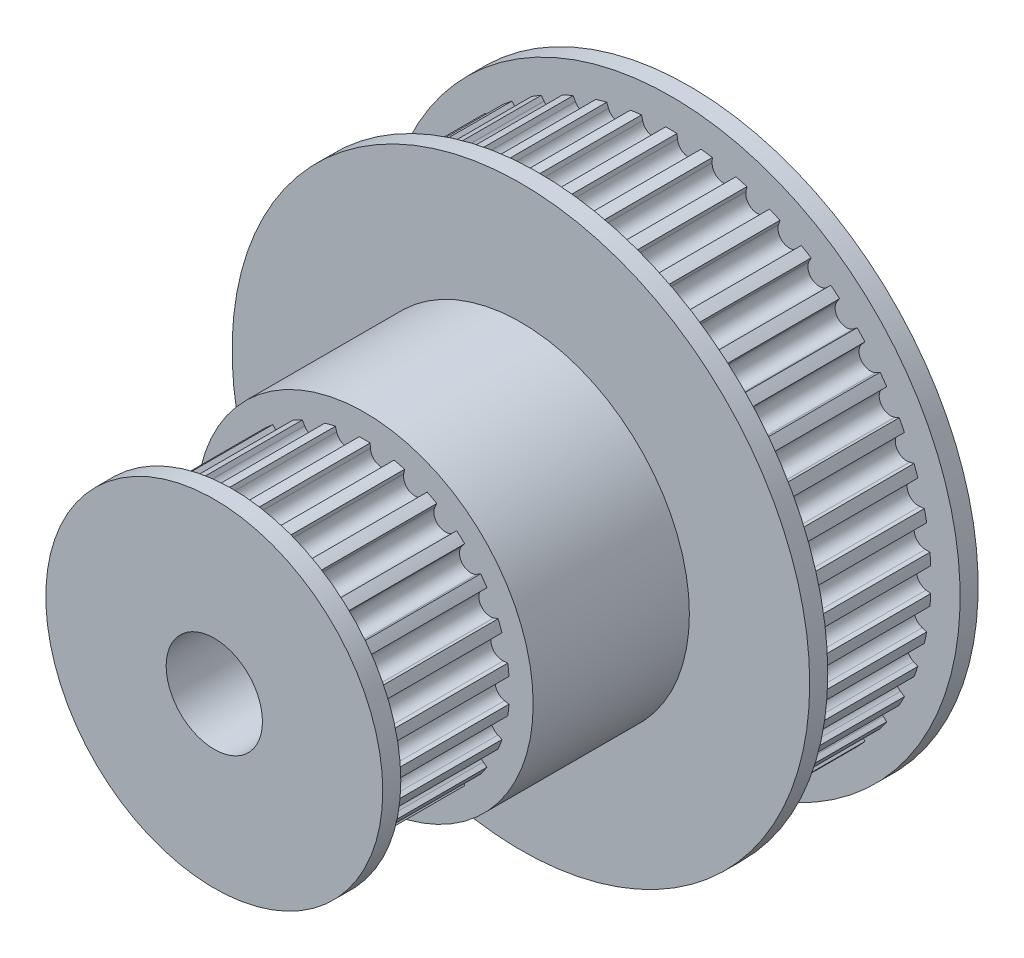
SolidWorks part; units mm, degrees
material "PLA Density Only"
ref_plane "Front Plane" through (0, 0, 0) normal (0, 0, 1) x (1, 0, 0)
ref_plane "Top Plane" through (0, 0, 0) normal (0, 1, 0) x (1, 0, 0)
ref_plane "Right Plane" through (0, 0, 0) normal (1, 0, 0) x (0, 0, -1)
sketch "Sketch1" plane through (0, 0, 0) normal (0, 0, 1) x (1, 0, 0)
  line L0 (-0.4734, 21.5748) -> (-0.5099, 21.1906)
  line L1 (-2.3803, 21.0626) -> (-2.4688, 21.4383)
  line L2 (-3.4068, 21.3094) -> (-3.3906, 20.9238)
  line L3 (-5.2262, 20.5423) -> (-5.3649, 20.9025)
  line L4 (-6.2767, 20.647) -> (-6.2081, 20.2672)
  line L5 (-7.9747, 19.6394) -> (-8.1612, 19.9773)
  line L6 (-9.0297, 19.6) -> (-8.91, 19.2331)
  line L7 (-10.5747, 18.3706) -> (-10.8054, 18.6799)
  line L8 (-11.6144, 18.188) -> (-11.4459, 17.8407)
  line L9 (-12.9776, 16.7595) -> (-13.2484, 17.0346)
  line L10 (-13.9828, 16.4371) -> (-13.7686, 16.116)
  line L11 (-15.1388, 14.8363) -> (-15.4445, 15.0719)
  line L12 (-16.0908, 14.38) -> (-15.8349, 14.0911)
  line L13 (-17.0181, 12.6367) -> (-17.353, 12.8285)
  line L14 (-17.899, 12.055) -> (-17.6061, 11.8037)
  line L15 (-18.5802, 10.2017) -> (-18.9381, 10.3462)
  line L16 (-19.3738, 9.5055) -> (-19.0494, 9.2964)
  line L17 (-19.7963, 7.5767) -> (-20.1706, 7.671)
  line L18 (-20.4876, 6.7789) -> (-20.1378, 6.6159)
  line L19 (-20.6436, 4.8105) -> (-21.0272, 4.853)
  line L20 (-21.2199, 3.926) -> (-20.8511, 3.8122)
  line L21 (-21.1064, 1.9548) -> (-21.4922, 1.9446)
  line L22 (-21.5568, 1) -> (-21.176, 0.9374)
  line L23 (-21.176, -0.9374) -> (-21.5568, -1)
  line L24 (-21.4922, -1.9446) -> (-21.1064, -1.9548)
  line L25 (-20.8511, -3.8122) -> (-21.2199, -3.926)
  line L26 (-21.0272, -4.853) -> (-20.6436, -4.8105)
  line L27 (-20.1378, -6.6159) -> (-20.4876, -6.7789)
  line L28 (-20.1706, -7.671) -> (-19.7963, -7.5767)
  line L29 (-19.0494, -9.2964) -> (-19.3738, -9.5055)
  line L30 (-18.9381, -10.3462) -> (-18.5802, -10.2017)
  line L31 (-17.6061, -11.8037) -> (-17.899, -12.055)
  line L32 (-17.353, -12.8285) -> (-17.0181, -12.6367)
  line L33 (-15.8349, -14.0911) -> (-16.0908, -14.38)
  line L34 (-15.4445, -15.0719) -> (-15.1388, -14.8363)
  line L35 (-13.7686, -16.116) -> (-13.9828, -16.4371)
  line L36 (-13.2484, -17.0346) -> (-12.9776, -16.7595)
  line L37 (-11.4459, -17.8407) -> (-11.6144, -18.188)
  line L38 (-10.8054, -18.6799) -> (-10.5747, -18.3706)
  line L39 (-8.91, -19.2331) -> (-9.0297, -19.6)
  line L40 (-8.1612, -19.9773) -> (-7.9747, -19.6394)
  line L41 (-6.2081, -20.2672) -> (-6.2767, -20.647)
  line L42 (-5.3649, -20.9025) -> (-5.2262, -20.5423)
  line L43 (-3.3906, -20.9238) -> (-3.4068, -21.3094)
  line L44 (-2.4688, -21.4383) -> (-2.3803, -21.0626)
  line L45 (-0.5099, -21.1906) -> (-0.4734, -21.5748)
  line L46 (0.4734, -21.5748) -> (0.5099, -21.1906)
  line L47 (2.3803, -21.0626) -> (2.4688, -21.4383)
  line L48 (3.4068, -21.3094) -> (3.3906, -20.9238)
  line L49 (5.2262, -20.5423) -> (5.3649, -20.9025)
  line L50 (6.2767, -20.647) -> (6.2081, -20.2672)
  line L51 (7.9747, -19.6394) -> (8.1612, -19.9773)
  line L52 (9.0297, -19.6) -> (8.91, -19.2331)
  line L53 (10.5747, -18.3706) -> (10.8054, -18.6799)
  line L54 (11.6144, -18.188) -> (11.4459, -17.8407)
  line L55 (12.9776, -16.7595) -> (13.2484, -17.0346)
  line L56 (13.9828, -16.4371) -> (13.7686, -16.116)
  line L57 (15.1388, -14.8363) -> (15.4445, -15.0719)
  line L58 (16.0908, -14.38) -> (15.8349, -14.0911)
  line L59 (17.0181, -12.6367) -> (17.353, -12.8285)
  line L60 (17.899, -12.055) -> (17.6061, -11.8037)
  line L61 (18.5802, -10.2017) -> (18.9381, -10.3462)
  line L62 (19.3738, -9.5055) -> (19.0494, -9.2964)
  line L63 (19.7963, -7.5767) -> (20.1706, -7.671)
  line L64 (20.4876, -6.7789) -> (20.1378, -6.6159)
  line L65 (20.6436, -4.8105) -> (21.0272, -4.853)
  line L66 (21.2199, -3.926) -> (20.8511, -3.8122)
  line L67 (21.1064, -1.9548) -> (21.4922, -1.9446)
  line L68 (21.5568, -1) -> (21.176, -0.9374)
  line L69 (21.176, 0.9374) -> (21.5568, 1)
  line L70 (21.4922, 1.9446) -> (21.1064, 1.9548)
  line L71 (20.8511, 3.8122) -> (21.2199, 3.926)
  line L72 (21.0272, 4.853) -> (20.6436, 4.8105)
  line L73 (20.1378, 6.6159) -> (20.4876, 6.7789)
  line L74 (20.1706, 7.671) -> (19.7963, 7.5767)
  line L75 (19.0494, 9.2964) -> (19.3738, 9.5055)
  line L76 (18.9381, 10.3462) -> (18.5802, 10.2017)
  line L77 (17.6061, 11.8037) -> (17.899, 12.055)
  line L78 (17.353, 12.8285) -> (17.0181, 12.6367)
  line L79 (15.8349, 14.0911) -> (16.0908, 14.38)
  line L80 (15.4445, 15.0719) -> (15.1388, 14.8363)
  line L81 (13.7686, 16.116) -> (13.9828, 16.4371)
  line L82 (13.2484, 17.0346) -> (12.9776, 16.7595)
  line L83 (11.4459, 17.8407) -> (11.6144, 18.188)
  line L84 (10.8054, 18.6799) -> (10.5747, 18.3706)
  line L85 (8.91, 19.2331) -> (9.0297, 19.6)
  line L86 (8.1612, 19.9773) -> (7.9747, 19.6394)
  line L87 (6.2081, 20.2672) -> (6.2767, 20.647)
  line L88 (5.3649, 20.9025) -> (5.2262, 20.5423)
  line L89 (3.3906, 20.9238) -> (3.4068, 21.3094)
  line L90 (2.4688, 21.4383) -> (2.3803, 21.0626)
  line L91 (0.5099, 21.1906) -> (0.4734, 21.5748)
  circle A0 centre (0, 0) radius 4
  arc A1 (-0.5099, 21.1906) -> (-2.3803, 21.0626) centre (-1.4556, 21.2803) cw
  arc A2 (-2.4688, 21.4383) -> (-3.4068, 21.3094) centre (0, 0) ccw
  arc A3 (-3.3906, 20.9238) -> (-5.2262, 20.5423) centre (-4.3397, 20.8839) cw
  arc A4 (-5.3649, 20.9025) -> (-6.2767, 20.647) centre (0, 0) ccw
  arc A5 (-6.2081, 20.2672) -> (-7.9747, 19.6394) centre (-7.143, 20.0984) cw
  arc A6 (-8.1612, 19.9773) -> (-9.0297, 19.6) centre (0, 0) ccw
  arc A7 (-8.91, 19.2331) -> (-10.5747, 18.3706) centre (-9.8132, 18.9386) cw
  arc A8 (-10.8054, 18.6799) -> (-11.6144, 18.188) centre (0, 0) ccw
  arc A9 (-11.4459, 17.8407) -> (-12.9776, 16.7595) centre (-12.3006, 17.426) cw
  arc A10 (-13.2484, 17.0346) -> (-13.9828, 16.4371) centre (0, 0) ccw
  arc A11 (-13.7686, 16.116) -> (-15.1388, 14.8363) centre (-14.5589, 15.5887) cw
  arc A12 (-15.4445, 15.0719) -> (-16.0908, 14.38) centre (0, 0) ccw
  arc A13 (-15.8349, 14.0911) -> (-17.0181, 12.6367) centre (-16.5459, 13.4611) cw
  arc A14 (-17.353, 12.8285) -> (-17.899, 12.055) centre (0, 0) ccw
  arc A15 (-17.6061, 11.8037) -> (-18.5802, 10.2017) centre (-18.2248, 11.0827) cw
  arc A16 (-18.9381, 10.3462) -> (-19.3738, 9.5055) centre (0, 0) ccw
  arc A17 (-19.0494, 9.2964) -> (-19.7963, 7.5767) centre (-19.5641, 8.4979) cw
  arc A18 (-20.1706, 7.671) -> (-20.4876, 6.7789) centre (0, 0) ccw
  arc A19 (-20.1378, 6.6159) -> (-20.6436, 4.8105) centre (-20.539, 5.7548) cw
  arc A20 (-21.0272, 4.853) -> (-21.2199, 3.926) centre (0, 0) ccw
  arc A21 (-20.8511, 3.8122) -> (-21.1064, 1.9548) centre (-21.1313, 2.9044) cw
  arc A22 (-21.4922, 1.9446) -> (-21.5568, 1) centre (0, 0) ccw
  arc A23 (-21.176, 0.9374) -> (-21.176, -0.9374) centre (-21.33, 0) cw
  arc A24 (-21.5568, -1) -> (-21.4922, -1.9446) centre (0, 0) ccw
  arc A25 (-21.1064, -1.9548) -> (-20.8511, -3.8122) centre (-21.1313, -2.9044) cw
  arc A26 (-21.2199, -3.926) -> (-21.0272, -4.853) centre (0, 0) ccw
  arc A27 (-20.6436, -4.8105) -> (-20.1378, -6.6159) centre (-20.539, -5.7548) cw
  arc A28 (-20.4876, -6.7789) -> (-20.1706, -7.671) centre (0, 0) ccw
  arc A29 (-19.7963, -7.5767) -> (-19.0494, -9.2964) centre (-19.5641, -8.4979) cw
  arc A30 (-19.3738, -9.5055) -> (-18.9381, -10.3462) centre (0, 0) ccw
  arc A31 (-18.5802, -10.2017) -> (-17.6061, -11.8037) centre (-18.2248, -11.0827) cw
  arc A32 (-17.899, -12.055) -> (-17.353, -12.8285) centre (0, 0) ccw
  arc A33 (-17.0181, -12.6367) -> (-15.8349, -14.0911) centre (-16.5459, -13.4611) cw
  arc A34 (-16.0908, -14.38) -> (-15.4445, -15.0719) centre (0, 0) ccw
  arc A35 (-15.1388, -14.8363) -> (-13.7686, -16.116) centre (-14.5589, -15.5887) cw
  arc A36 (-13.9828, -16.4371) -> (-13.2484, -17.0346) centre (0, 0) ccw
  arc A37 (-12.9776, -16.7595) -> (-11.4459, -17.8407) centre (-12.3006, -17.426) cw
  arc A38 (-11.6144, -18.188) -> (-10.8054, -18.6799) centre (0, 0) ccw
  arc A39 (-10.5747, -18.3706) -> (-8.91, -19.2331) centre (-9.8132, -18.9386) cw
  arc A40 (-9.0297, -19.6) -> (-8.1612, -19.9773) centre (0, 0) ccw
  arc A41 (-7.9747, -19.6394) -> (-6.2081, -20.2672) centre (-7.143, -20.0984) cw
  arc A42 (-6.2767, -20.647) -> (-5.3649, -20.9025) centre (0, 0) ccw
  arc A43 (-5.2262, -20.5423) -> (-3.3906, -20.9238) centre (-4.3397, -20.8839) cw
  arc A44 (-3.4068, -21.3094) -> (-2.4688, -21.4383) centre (0, 0) ccw
  arc A45 (-2.3803, -21.0626) -> (-0.5099, -21.1906) centre (-1.4556, -21.2803) cw
  arc A46 (-0.4734, -21.5748) -> (0.4734, -21.5748) centre (0, 0) ccw
  arc A47 (0.5099, -21.1906) -> (2.3803, -21.0626) centre (1.4556, -21.2803) cw
  arc A48 (2.4688, -21.4383) -> (3.4068, -21.3094) centre (0, 0) ccw
  arc A49 (3.3906, -20.9238) -> (5.2262, -20.5423) centre (4.3397, -20.8839) cw
  arc A50 (5.3649, -20.9025) -> (6.2767, -20.647) centre (0, 0) ccw
  arc A51 (6.2081, -20.2672) -> (7.9747, -19.6394) centre (7.143, -20.0984) cw
  arc A52 (8.1612, -19.9773) -> (9.0297, -19.6) centre (0, 0) ccw
  arc A53 (8.91, -19.2331) -> (10.5747, -18.3706) centre (9.8132, -18.9386) cw
  arc A54 (10.8054, -18.6799) -> (11.6144, -18.188) centre (0, 0) ccw
  arc A55 (11.4459, -17.8407) -> (12.9776, -16.7595) centre (12.3006, -17.426) cw
  arc A56 (13.2484, -17.0346) -> (13.9828, -16.4371) centre (0, 0) ccw
  arc A57 (13.7686, -16.116) -> (15.1388, -14.8363) centre (14.5589, -15.5887) cw
  arc A58 (15.4445, -15.0719) -> (16.0908, -14.38) centre (0, 0) ccw
  arc A59 (15.8349, -14.0911) -> (17.0181, -12.6367) centre (16.5459, -13.4611) cw
  arc A60 (17.353, -12.8285) -> (17.899, -12.055) centre (0, 0) ccw
  arc A61 (17.6061, -11.8037) -> (18.5802, -10.2017) centre (18.2248, -11.0827) cw
  arc A62 (18.9381, -10.3462) -> (19.3738, -9.5055) centre (0, 0) ccw
  arc A63 (19.0494, -9.2964) -> (19.7963, -7.5767) centre (19.5641, -8.4979) cw
  arc A64 (20.1706, -7.671) -> (20.4876, -6.7789) centre (0, 0) ccw
  arc A65 (20.1378, -6.6159) -> (20.6436, -4.8105) centre (20.539, -5.7548) cw
  arc A66 (21.0272, -4.853) -> (21.2199, -3.926) centre (0, 0) ccw
  arc A67 (20.8511, -3.8122) -> (21.1064, -1.9548) centre (21.1313, -2.9044) cw
  arc A68 (21.4922, -1.9446) -> (21.5568, -1) centre (0, 0) ccw
  arc A69 (21.176, -0.9374) -> (21.176, 0.9374) centre (21.33, 0) cw
  arc A70 (21.5568, 1) -> (21.4922, 1.9446) centre (0, 0) ccw
  arc A71 (21.1064, 1.9548) -> (20.8511, 3.8122) centre (21.1313, 2.9044) cw
  arc A72 (21.2199, 3.926) -> (21.0272, 4.853) centre (0, 0) ccw
  arc A73 (20.6436, 4.8105) -> (20.1378, 6.6159) centre (20.539, 5.7548) cw
  arc A74 (20.4876, 6.7789) -> (20.1706, 7.671) centre (0, 0) ccw
  arc A75 (19.7963, 7.5767) -> (19.0494, 9.2964) centre (19.5641, 8.4979) cw
  arc A76 (19.3738, 9.5055) -> (18.9381, 10.3462) centre (0, 0) ccw
  arc A77 (18.5802, 10.2017) -> (17.6061, 11.8037) centre (18.2248, 11.0827) cw
  arc A78 (17.899, 12.055) -> (17.353, 12.8285) centre (0, 0) ccw
  arc A79 (17.0181, 12.6367) -> (15.8349, 14.0911) centre (16.5459, 13.4611) cw
  arc A80 (16.0908, 14.38) -> (15.4445, 15.0719) centre (0, 0) ccw
  arc A81 (15.1388, 14.8363) -> (13.7686, 16.116) centre (14.5589, 15.5887) cw
  arc A82 (13.9828, 16.4371) -> (13.2484, 17.0346) centre (0, 0) ccw
  arc A83 (12.9776, 16.7595) -> (11.4459, 17.8407) centre (12.3006, 17.426) cw
  arc A84 (11.6144, 18.188) -> (10.8054, 18.6799) centre (0, 0) ccw
  arc A85 (10.5747, 18.3706) -> (8.91, 19.2331) centre (9.8132, 18.9386) cw
  arc A86 (9.0297, 19.6) -> (8.1612, 19.9773) centre (0, 0) ccw
  arc A87 (7.9747, 19.6394) -> (6.2081, 20.2672) centre (7.143, 20.0984) cw
  arc A88 (6.2767, 20.647) -> (5.3649, 20.9025) centre (0, 0) ccw
  arc A89 (5.2262, 20.5423) -> (3.3906, 20.9238) centre (4.3397, 20.8839) cw
  arc A90 (3.4068, 21.3094) -> (2.4688, 21.4383) centre (0, 0) ccw
  arc A91 (2.3803, 21.0626) -> (0.5099, 21.1906) centre (1.4556, 21.2803) cw
  arc A92 (0.4734, 21.5748) -> (-0.4734, 21.5748) centre (0, 0) ccw
extrude "Boss-Extrude1" add sketch "Sketch1" along normal blind 11
ref_plane "Plane1" through (0, 0, 36.48) normal (0, 0, 1) x (1, 0, 0)
sketch "Sketch2" plane through (0, 0, 36.48) normal (0, 0, 1) x (1, 0, 0)
  line L0 (-0.4529, 12.0265) -> (-0.4717, 11.6515)
  line L1 (-2.3304, 11.4259) -> (-2.4384, 11.7854)
  line L2 (-3.3179, 11.5686) -> (-3.2464, 11.2001)
  line L3 (-4.9971, 10.5361) -> (-5.1879, 10.8594)
  line L4 (-5.99, 10.4384) -> (-5.8324, 10.0977)
  line L5 (-7.3733, 9.0341) -> (-7.636, 9.3023)
  line L6 (-8.3141, 8.7016) -> (-8.0795, 8.4085)
  line L7 (-9.3211, 7.007) -> (-9.6403, 7.2046)
  line L8 (-10.1549, 6.4591) -> (-9.857, 6.2306)
  line L9 (-10.7271, 4.5728) -> (-11.0843, 4.6881)
  line L10 (-11.4056, 3.8411) -> (-11.0617, 3.6906)
  line L11 (-11.5097, 1.8727) -> (-11.8842, 1.8993)
  line L12 (-11.9934, 1) -> (-11.6235, 0.9362)
  line L13 (-11.6235, -0.9362) -> (-11.9934, -1)
  line L14 (-11.8842, -1.8993) -> (-11.5097, -1.8727)
  line L15 (-11.0617, -3.6906) -> (-11.4056, -3.8411)
  line L16 (-11.0843, -4.6881) -> (-10.7271, -4.5728)
  line L17 (-9.857, -6.2306) -> (-10.1549, -6.4591)
  line L18 (-9.6403, -7.2046) -> (-9.3211, -7.007)
  line L19 (-8.0795, -8.4085) -> (-8.3141, -8.7016)
  line L20 (-7.636, -9.3023) -> (-7.3733, -9.0341)
  line L21 (-5.8324, -10.0977) -> (-5.99, -10.4384)
  line L22 (-5.1879, -10.8594) -> (-4.9971, -10.5361)
  line L23 (-3.2464, -11.2001) -> (-3.3179, -11.5686)
  line L24 (-2.4384, -11.7854) -> (-2.3304, -11.4259)
  line L25 (-0.4717, -11.6515) -> (-0.4529, -12.0265)
  line L26 (0.4529, -12.0265) -> (0.4717, -11.6515)
  line L27 (2.3304, -11.4259) -> (2.4384, -11.7854)
  line L28 (3.3179, -11.5686) -> (3.2464, -11.2001)
  line L29 (4.9971, -10.5361) -> (5.1879, -10.8594)
  line L30 (5.99, -10.4384) -> (5.8324, -10.0977)
  line L31 (7.3733, -9.0341) -> (7.636, -9.3023)
  line L32 (8.3141, -8.7016) -> (8.0795, -8.4085)
  line L33 (9.3211, -7.007) -> (9.6403, -7.2046)
  line L34 (10.1549, -6.4591) -> (9.857, -6.2306)
  line L35 (10.7271, -4.5728) -> (11.0843, -4.6881)
  line L36 (11.4056, -3.8411) -> (11.0617, -3.6906)
  line L37 (11.5097, -1.8727) -> (11.8842, -1.8993)
  line L38 (11.9934, -1) -> (11.6235, -0.9362)
  line L39 (11.6235, 0.9362) -> (11.9934, 1)
  line L40 (11.8842, 1.8993) -> (11.5097, 1.8727)
  line L41 (11.0617, 3.6906) -> (11.4056, 3.8411)
  line L42 (11.0843, 4.6881) -> (10.7271, 4.5728)
  line L43 (9.857, 6.2306) -> (10.1549, 6.4591)
  line L44 (9.6403, 7.2046) -> (9.3211, 7.007)
  line L45 (8.0795, 8.4085) -> (8.3141, 8.7016)
  line L46 (7.636, 9.3023) -> (7.3733, 9.0341)
  line L47 (5.8324, 10.0977) -> (5.99, 10.4384)
  line L48 (5.1879, 10.8594) -> (4.9971, 10.5361)
  line L49 (3.2464, 11.2001) -> (3.3179, 11.5686)
  line L50 (2.4384, 11.7854) -> (2.3304, 11.4259)
  line L51 (0.4717, 11.6515) -> (0.4529, 12.0265)
  circle A0 centre (0, 0) radius 4
  arc A1 (-0.4717, 11.6515) -> (-2.3304, 11.4259) centre (-1.4205, 11.6991) cw
  arc A2 (-2.4384, 11.7854) -> (-3.3179, 11.5686) centre (0, 0) ccw
  arc A3 (-3.2464, 11.2001) -> (-4.9971, 10.5361) centre (-4.179, 11.0192) cw
  arc A4 (-5.1879, 10.8594) -> (-5.99, 10.4384) centre (0, 0) ccw
  arc A5 (-5.8324, 10.0977) -> (-7.3733, 9.0341) centre (-6.6946, 9.6989) cw
  arc A6 (-7.636, 9.3023) -> (-8.3141, 8.7016) centre (0, 0) ccw
  arc A7 (-8.0795, 8.4085) -> (-9.3211, 7.007) centre (-8.8212, 7.8149) cw
  arc A8 (-9.6403, 7.2046) -> (-10.1549, 6.4591) centre (0, 0) ccw
  arc A9 (-9.857, 6.2306) -> (-10.7271, 4.5728) centre (-10.4351, 5.4768) cw
  arc A10 (-11.0843, 4.6881) -> (-11.4056, 3.8411) centre (0, 0) ccw
  arc A11 (-11.0617, 3.6906) -> (-11.5097, 1.8727) centre (-11.4425, 2.8203) cw
  arc A12 (-11.8842, 1.8993) -> (-11.9934, 1) centre (0, 0) ccw
  arc A13 (-11.6235, 0.9362) -> (-11.6235, -0.9362) centre (-11.785, 0) cw
  arc A14 (-11.9934, -1) -> (-11.8842, -1.8993) centre (0, 0) ccw
  arc A15 (-11.5097, -1.8727) -> (-11.0617, -3.6906) centre (-11.4425, -2.8203) cw
  arc A16 (-11.4056, -3.8411) -> (-11.0843, -4.6881) centre (0, 0) ccw
  arc A17 (-10.7271, -4.5728) -> (-9.857, -6.2306) centre (-10.4351, -5.4768) cw
  arc A18 (-10.1549, -6.4591) -> (-9.6403, -7.2046) centre (0, 0) ccw
  arc A19 (-9.3211, -7.007) -> (-8.0795, -8.4085) centre (-8.8212, -7.8149) cw
  arc A20 (-8.3141, -8.7016) -> (-7.636, -9.3023) centre (0, 0) ccw
  arc A21 (-7.3733, -9.0341) -> (-5.8324, -10.0977) centre (-6.6946, -9.6989) cw
  arc A22 (-5.99, -10.4384) -> (-5.1879, -10.8594) centre (0, 0) ccw
  arc A23 (-4.9971, -10.5361) -> (-3.2464, -11.2001) centre (-4.179, -11.0192) cw
  arc A24 (-3.3179, -11.5686) -> (-2.4384, -11.7854) centre (0, 0) ccw
  arc A25 (-2.3304, -11.4259) -> (-0.4717, -11.6515) centre (-1.4205, -11.6991) cw
  arc A26 (-0.4529, -12.0265) -> (0.4529, -12.0265) centre (0, 0) ccw
  arc A27 (0.4717, -11.6515) -> (2.3304, -11.4259) centre (1.4205, -11.6991) cw
  arc A28 (2.4384, -11.7854) -> (3.3179, -11.5686) centre (0, 0) ccw
  arc A29 (3.2464, -11.2001) -> (4.9971, -10.5361) centre (4.179, -11.0192) cw
  arc A30 (5.1879, -10.8594) -> (5.99, -10.4384) centre (0, 0) ccw
  arc A31 (5.8324, -10.0977) -> (7.3733, -9.0341) centre (6.6946, -9.6989) cw
  arc A32 (7.636, -9.3023) -> (8.3141, -8.7016) centre (0, 0) ccw
  arc A33 (8.0795, -8.4085) -> (9.3211, -7.007) centre (8.8212, -7.8149) cw
  arc A34 (9.6403, -7.2046) -> (10.1549, -6.4591) centre (0, 0) ccw
  arc A35 (9.857, -6.2306) -> (10.7271, -4.5728) centre (10.4351, -5.4768) cw
  arc A36 (11.0843, -4.6881) -> (11.4056, -3.8411) centre (0, 0) ccw
  arc A37 (11.0617, -3.6906) -> (11.5097, -1.8727) centre (11.4425, -2.8203) cw
  arc A38 (11.8842, -1.8993) -> (11.9934, -1) centre (0, 0) ccw
  arc A39 (11.6235, -0.9362) -> (11.6235, 0.9362) centre (11.785, 0) cw
  arc A40 (11.9934, 1) -> (11.8842, 1.8993) centre (0, 0) ccw
  arc A41 (11.5097, 1.8727) -> (11.0617, 3.6906) centre (11.4425, 2.8203) cw
  arc A42 (11.4056, 3.8411) -> (11.0843, 4.6881) centre (0, 0) ccw
  arc A43 (10.7271, 4.5728) -> (9.857, 6.2306) centre (10.4351, 5.4768) cw
  arc A44 (10.1549, 6.4591) -> (9.6403, 7.2046) centre (0, 0) ccw
  arc A45 (9.3211, 7.007) -> (8.0795, 8.4085) centre (8.8212, 7.8149) cw
  arc A46 (8.3141, 8.7016) -> (7.636, 9.3023) centre (0, 0) ccw
  arc A47 (7.3733, 9.0341) -> (5.8324, 10.0977) centre (6.6946, 9.6989) cw
  arc A48 (5.99, 10.4384) -> (5.1879, 10.8594) centre (0, 0) ccw
  arc A49 (4.9971, 10.5361) -> (3.2464, 11.2001) centre (4.179, 11.0192) cw
  arc A50 (3.3179, 11.5686) -> (2.4384, 11.7854) centre (0, 0) ccw
  arc A51 (2.3304, 11.4259) -> (0.4717, 11.6515) centre (1.4205, 11.6991) cw
  arc A52 (0.4529, 12.0265) -> (-0.4529, 12.0265) centre (0, 0) ccw
extrude "Boss-Extrude2" add sketch "Sketch2" against normal blind 11 separate body
sketch "Sketch3" plane through (0, 0, 0) normal (0, 0, -1) x (-1, 0, 0)
  circle A0 centre (0, 0) radius 24
  dimension "D1" = 48
extrude "Boss-Extrude3" add sketch "Sketch3" along normal blind 1.5
sketch "Sketch4" plane through (0, 0, 11) normal (0, 0, 1) x (1, 0, 0)
  circle A0 centre (0, 0) radius 24
extrude "Boss-Extrude4" add sketch "Sketch4" along normal blind 1.5
sketch "Sketch5" plane through (0, 0, 36.48) normal (0, 0, 1) x (1, 0, 0)
  circle A0 centre (0, 0) radius 14
  dimension "D1" = 28
extrude "Boss-Extrude5" add sketch "Sketch5" along normal blind 1.5
sketch "Sketch6" plane through (0, 0, 25.48) normal (0, 0, -1) x (-1, 0, 0)
  circle A0 centre (0, 0) radius 14
  dimension "D1" = 28
extrude "Boss-Extrude6" add sketch "Sketch6" along normal up to surface (12.98 mm away) up to face at (24, 0, 12.5)
sketch "Sketch7" plane through (0, 0, -1.5) normal (0, 0, -1) x (-1, 0, 0)
  circle A0 centre (0, 0) radius 4
  dimension "D1" = 8
extrude "Cut-Extrude1" cut sketch "Sketch7" against normal through all both and the other way through all
